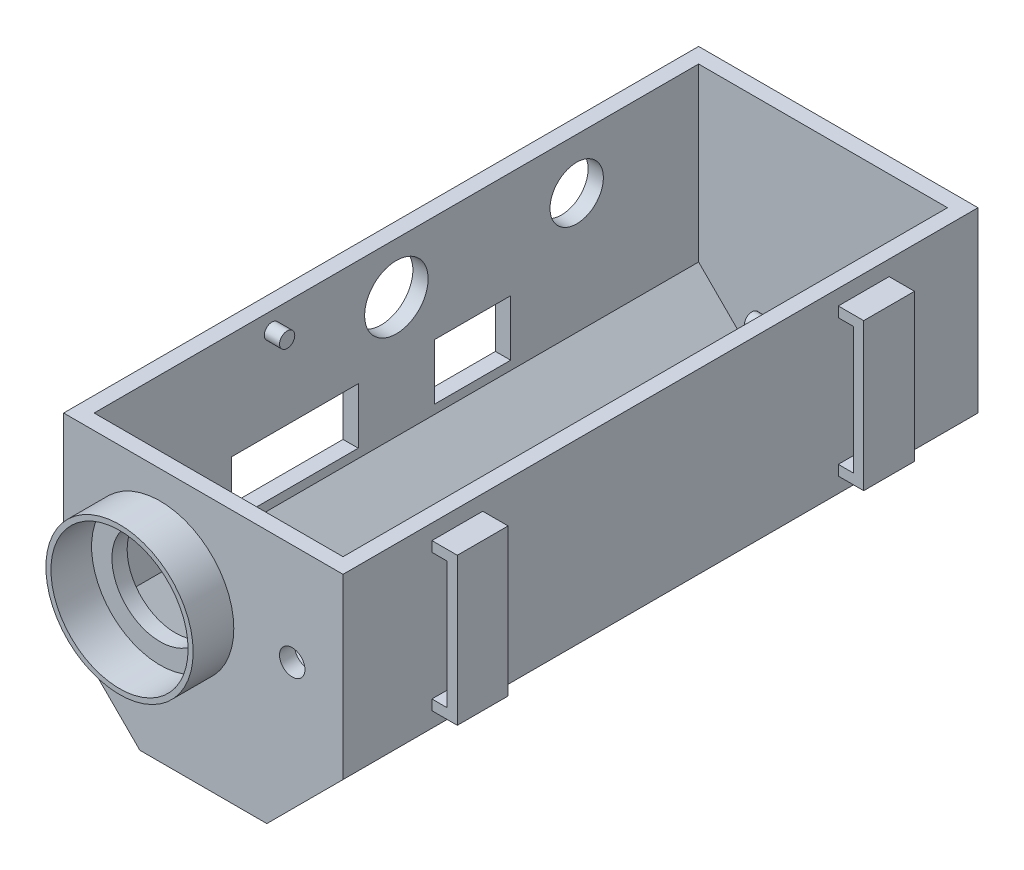
SolidWorks part; units mm, degrees
ref_plane "Front Plane" through (0, 0, 0) normal (0, 0, 1) x (1, 0, 0)
ref_plane "Top Plane" through (0, 0, 0) normal (0, 1, 0) x (1, 0, 0)
ref_plane "Right Plane" through (0, 0, 0) normal (1, 0, 0) x (0, 0, -1)
sketch "Sketch1" plane through (0, 0, 0) normal (0, 1, 0) x (1, 0, 0)
  line L1 (0, 0) -> (55, 0)
  line L2 (0, 0) -> (0, -125)
  line L3 (0, -125) -> (55, -125)
  line L4 (55, 0) -> (55, -125)
  dimension "D1" = 125
  dimension "D2" = 55
extrude "Boss-Extrude1" add sketch "Sketch1" along normal blind 50
fillet "Fillet1" radius 15 1 edges at (55, 0, 62.5) profile chamfer
chamfer "Chamfer1" distance 15 angle 45 1 edges at (0, 0, 62.5)
shell "Shell1" thickness 3
sketch "Sketch11" plane through (55, 0, 0) normal (1, 0, 0) x (0, 0, -1)
  line L0 (-125, 15) -> (0, 15) construction
  line L1 (-107.5, 47) -> (-97.5, 47)
  line L2 (-107.5, 47) -> (-107.5, 18)
  line L3 (-107.5, 18) -> (-97.5, 18)
  line L4 (-97.5, 47) -> (-97.5, 18)
  line L5 (-27.5, 47) -> (-17.5, 47)
  line L6 (-27.5, 47) -> (-27.5, 18)
  line L7 (-27.5, 18) -> (-17.5, 18)
  line L8 (-17.5, 47) -> (-17.5, 18)
  line L9 (0, 50) -> (0, 15) construction
  point P8 (-22.5, 18)
  dimension "D1" = 10
  dimension "D2" = 10
  dimension "D3" = 29
  dimension "D4" = 29
  dimension "D5" = 3
  dimension "D6" = 3
  dimension "D7" = 70
  dimension "D8" = 17.5
extrude "Boss-Extrude3" add sketch "Sketch11" along normal blind 5
sketch "Sketch12" plane through (0, 0, 107.5) normal (0, 0, 1) x (1, 0, 0)
  line L0 (55, 47) -> (55, 18) construction
  line L1 (58, 45) -> (55, 45)
  line L2 (58, 45) -> (58, 20)
  line L3 (58, 20) -> (55, 20)
  line L4 (55, 45) -> (55, 20)
  line L5 (60, 47) -> (55, 47) construction
  line L6 (60, 18) -> (55, 18) construction
  line L8 (60, 47) -> (60, 18) construction
  dimension "D1" = 2
  dimension "D2" = 2
  dimension "D3" = 2
extrude "Cut-Extrude2" cut sketch "Sketch12" against normal through all both and the other way through all contours L2 L3 L4 L1
sketch "Sketch31" plane through (0, 0, 125) normal (0, 0, 1) x (1, 0, 0)
  line L0 (55, 50) -> (55, 15) construction
  line L1 (15, 0) -> (40, 0) construction
  circle A0 centre (19, 30) radius 14.5
  dimension "D1" = 29
  dimension "D2" = 36
  dimension "D3" = 30
extrude "Boss-Extrude10" add sketch "Sketch31" along normal blind 8
sketch "Sketch32" plane through (0, 0, 133) normal (0, 0, 1) x (1, 0, 0)
  circle A0 centre (19, 30) radius 13.5
  circle A1 centre (19, 30) radius 14.5 construction
  dimension "D1" = 27
  dimension "D2" = 0
extrude "Cut-Extrude11" cut sketch "Sketch32" against normal blind 8
sketch "Sketch33" plane through (0, 0, 125) normal (0, 0, 1) x (1, 0, 0)
  circle A0 centre (19, 30) radius 9.5
  dimension "D1" = 19
extrude "Cut-Extrude12" cut sketch "Sketch33" against normal blind 20
sketch "Sketch34" plane through (0, 0, 125) normal (0, 0, 1) x (1, 0, 0)
  line L0 (15, 0) -> (40, 0) construction
  line L1 (55, 50) -> (55, 15) construction
  circle A0 centre (45, 30) radius 2.5
  dimension "D1" = 5
  dimension "D2" = 30
  dimension "D3" = 10
extrude "Cut-Extrude15" cut sketch "Sketch34" against normal blind 5
sketch "Sketch39" plane through (0, 0, 0) normal (-1, 0, 0) x (0, 0, 1)
  line L0 (125, 50) -> (125, 15) construction
  line L1 (40, 29) -> (55, 29)
  line L2 (40, 29) -> (40, 18)
  line L3 (40, 18) -> (55, 18)
  line L4 (55, 29) -> (55, 18)
  line L9 (70, 29) -> (95, 29)
  line L10 (70, 29) -> (70, 18)
  line L11 (70, 18) -> (95, 18)
  line L12 (95, 29) -> (95, 18)
  line L13 (0, 15) -> (125, 15) construction
  dimension "D1" = 15
  dimension "D2" = 15
  dimension "D3" = 25
  dimension "D4" = 11
  dimension "D5" = 11
  dimension "D6" = 30
  dimension "D7" = 3
  dimension "D8" = 3
extrude "Cut-Extrude16" cut sketch "Sketch39" against normal blind 10
sketch "Sketch41" plane through (0, 0, 0) normal (-1, 0, 0) x (0, 0, 1)
  line L0 (125, 50) -> (125, 15) construction
  line L1 (0, 50) -> (0, 15) construction
  line L2 (0, 15) -> (125, 15) construction
  circle A0 centre (62.5, 40) radius 6.25
  circle A1 centre (27, 40) radius 5.25
  dimension "D1" = 12.5
  dimension "D2" = 10.5
  dimension "D3" = 62.5
  dimension "D4" = 27
  dimension "D5" = 25
  dimension "D6" = 25
extrude "Cut-Extrude17" cut sketch "Sketch41" against normal blind 10
sketch "Sketch44" plane through (3, 0, 0) normal (1, 0, 0) x (0, 0, -1)
  line L0 (-122, 50) -> (-122, 16.2426) construction
  line L1 (-3, 50) -> (-122, 50) construction
  circle A0 centre (-87, 46.5) radius 1.5
  dimension "D1" = 3
  dimension "D2" = 35
  dimension "D3" = 3.5
extrude "Boss-Extrude11" add sketch "Sketch44" along normal blind 3
sketch "Sketch45" plane through (52, 0, 0) normal (-1, 0, 0) x (0, 0, 1)
  line L0 (3, 50) -> (3, 16.2426) construction
  line L1 (122, 50) -> (3, 50) construction
  circle A0 centre (38, 46.5) radius 1.5
  dimension "D1" = 3
  dimension "D2" = 35
  dimension "D3" = 3.5
extrude "Boss-Extrude12" add sketch "Sketch45" along normal blind 3.5
